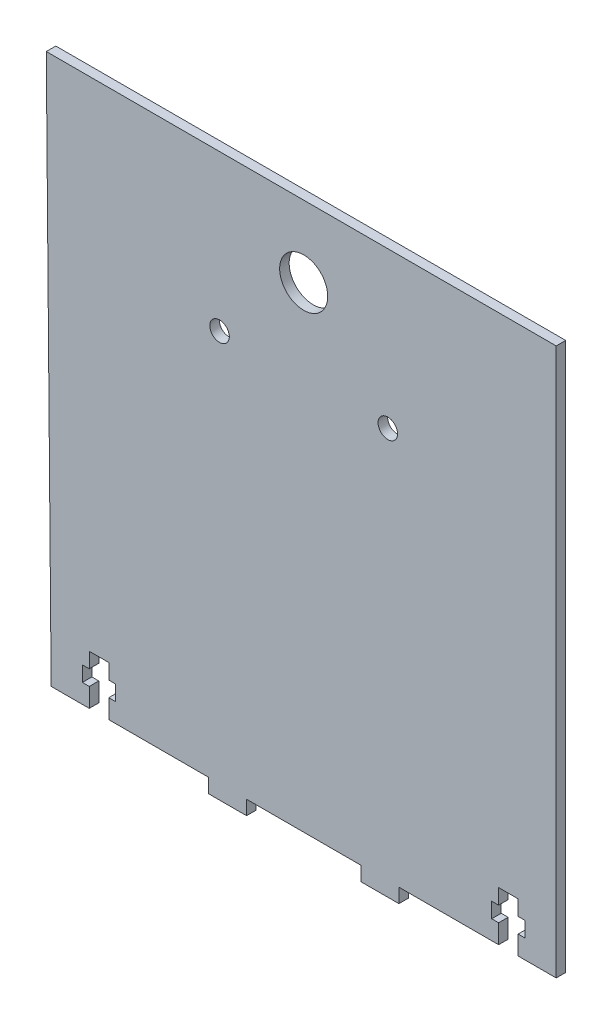
SolidWorks part; units mm, degrees
ref_plane "前视基准面" through (0, 0, 0) normal (0, 0, 1) x (1, 0, 0)
ref_plane "上视基准面" through (0, 0, 0) normal (0, 1, 0) x (1, 0, 0)
ref_plane "右视基准面" through (0, 0, 0) normal (1, 0, 0) x (0, 0, -1)
sketch "草图1" plane through (0, 0, 0) normal (0, 0, 1) x (1, 0, 0)
  line L0 (-42.7912, 3.1303) -> (43.2088, 3.1303) construction
  line L1 (-42.7912, 3.1303) -> (-42.7912, 5.1553) construction
  line L2 (-40.7412, 3.1303) -> (-40.7412, 7.1303)
  line L3 (-40.7412, 7.1303) -> (-39.2912, 7.1303)
  line L4 (-39.2912, 7.1303) -> (-39.2912, 10.3303)
  line L5 (-39.2912, 10.3303) -> (-40.7412, 10.3303)
  line L6 (-40.7412, 10.3303) -> (-40.7412, 13.5303)
  line L7 (-40.7412, 13.5303) -> (-44.8412, 13.5303)
  line L8 (-46.2912, 7.1303) -> (-46.2912, 10.3303)
  line L9 (-44.8412, 10.3303) -> (-44.8412, 13.5303)
  line L10 (-44.8412, 3.1303) -> (-44.8412, 7.1303)
  line L11 (-44.8412, 7.1303) -> (-46.2912, 7.1303)
  line L12 (-46.2912, 10.3303) -> (-44.8412, 10.3303)
  line L15 (-19.7912, 3.1303) -> (-19.7912, 0.1303)
  line L16 (-19.7912, 0.1303) -> (-11.7912, 0.1303)
  line L17 (-11.7912, 0.1303) -> (-11.7912, 3.1303)
  line L18 (-15.7912, 0.1303) -> (-15.7912, 3.1303) construction
  line L19 (-40.7412, 3.1303) -> (-19.7912, 3.1303)
  line L20 (0.2088, 3.1303) -> (0.2088, -7.8241) construction
  line L22 (-44.8412, 3.1303) -> (-52.8412, 3.1303)
  line L23 (-52.8412, 3.1303) -> (-53.8708, 118.1303)
  line L42 (0.2088, 3.1303) -> (0.2088, 103.1303) construction
  line L43 (0.2088, 103.1303) -> (57.1498, 46.1893) construction
  line L44 (16.2088, 0.1303) -> (16.2088, 3.1303) construction
  line L45 (43.2088, 3.1303) -> (43.2088, 5.1553) construction
  line L46 (45.2588, 3.1303) -> (53.2588, 3.1303)
  line L47 (41.1588, 3.1303) -> (20.2088, 3.1303)
  line L48 (12.2088, 0.1303) -> (12.2088, 3.1303)
  line L49 (20.2088, 0.1303) -> (12.2088, 0.1303)
  line L50 (20.2088, 3.1303) -> (20.2088, 0.1303)
  line L51 (46.7088, 10.3303) -> (45.2588, 10.3303)
  line L52 (45.2588, 7.1303) -> (46.7088, 7.1303)
  line L53 (45.2588, 3.1303) -> (45.2588, 7.1303)
  line L54 (45.2588, 10.3303) -> (45.2588, 13.5303)
  line L55 (46.7088, 7.1303) -> (46.7088, 10.3303)
  line L56 (41.1588, 13.5303) -> (45.2588, 13.5303)
  line L57 (41.1588, 10.3303) -> (41.1588, 13.5303)
  line L58 (39.7088, 10.3303) -> (41.1588, 10.3303)
  line L59 (39.7088, 7.1303) -> (39.7088, 10.3303)
  line L60 (41.1588, 7.1303) -> (39.7088, 7.1303)
  line L61 (41.1588, 3.1303) -> (41.1588, 7.1303)
  line L62 (-11.7912, 3.1303) -> (12.2088, 3.1303)
  line L64 (-53.8708, 118.1303) -> (43.5828, 118.1303)
  line L65 (53.2588, 3.1303) -> (53.2588, 118.1303)
  line L66 (53.2588, 118.1303) -> (43.5828, 118.1303)
  circle A0 centre (0.2088, 103.1303) radius 5.05
  circle A1 centre (0.2088, 103.1303) radius 25 construction
  circle A2 centre (17.8865, 85.4526) radius 2.05
  circle A3 centre (-17.4689, 85.4526) radius 2.05
  point P16 (-42.7912, 13.5303)
  point P56 (43.2088, 13.5303)
  dimension "D10" = 10.1
  dimension "D13" = 50
  dimension "D14" = 4.1
  dimension "D2" = 2.05
  dimension "D3" = 3.2
  dimension "D4" = 4
  dimension "D5" = 3.5
  dimension "D6" = 8
  dimension "D7" = 3
  dimension "D8" = 27
  dimension "D9" = 12
  dimension "D11" = 100
  dimension "D12" = 45
  dimension "D15" = 8
  dimension "D16" = 15
extrude "凸台-拉伸1" add sketch "草图1" along normal blind 2
sketch "草图2" plane through (0, 3.1303, 0) normal (0, -1, 0) x (1, 0, 0)
  line L0 (41.1588, 1) -> (45.2588, 1)
  line L1 (41.1588, 2) -> (41.1588, 0) construction
  line L2 (45.2588, 2) -> (45.2588, 0) construction
  circle A0 centre (43.2088, 1) radius 2.05
